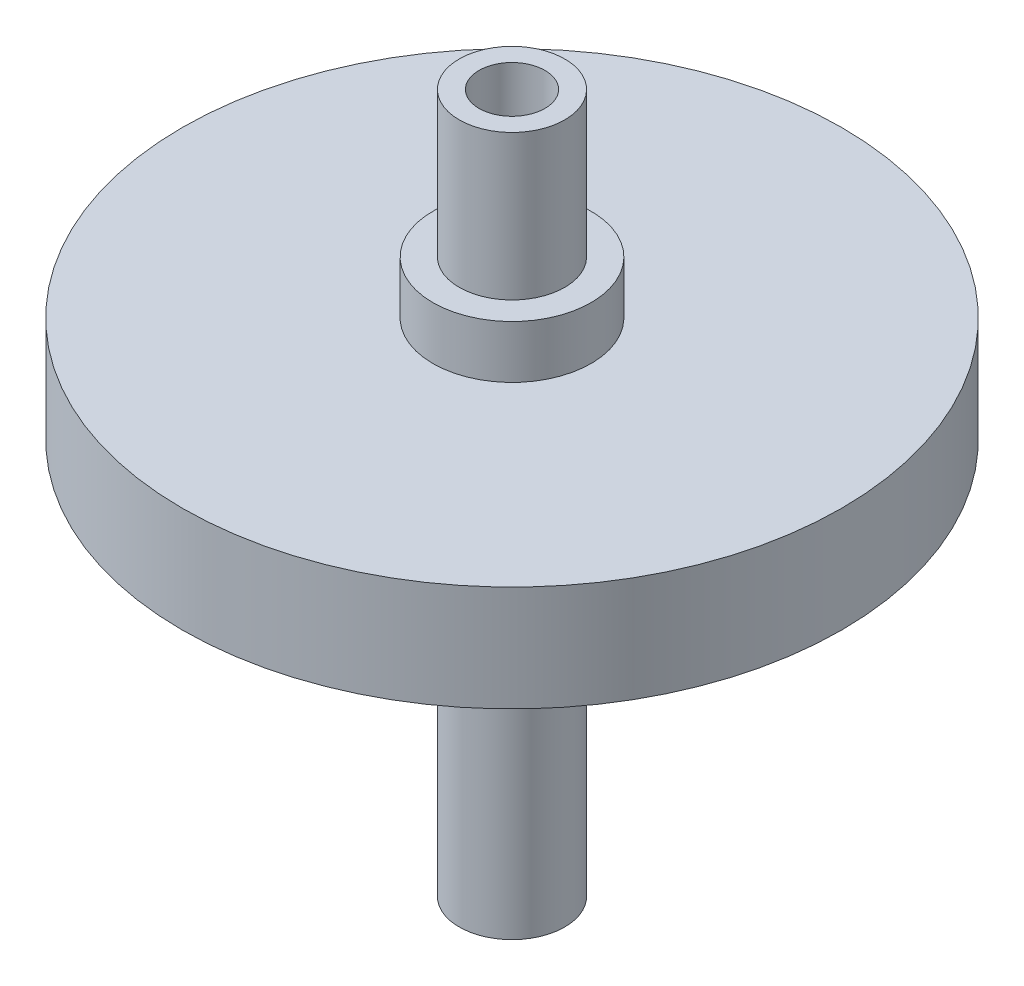
SolidWorks part; units mm, degrees
ref_plane "Front Plane" through (0, 0, 0) normal (0, 0, 1) x (1, 0, 0)
ref_plane "Top Plane" through (0, 0, 0) normal (0, 1, 0) x (1, 0, 0)
ref_plane "Right Plane" through (0, 0, 0) normal (1, 0, 0) x (0, 0, -1)
sketch "Sketch1" plane through (0, 0, 0) normal (0, 1, 0) x (1, 0, 0)
  circle A0 centre (0, 0) radius 25
  dimension "D1" = 50
extrude "Boss-Extrude1" add sketch "Sketch1" along normal blind 8
sketch "Sketch2" plane through (0, 8, 0) normal (0, 1, 0) x (1, 0, 0)
  circle A0 centre (0, 0) radius 4
extrude "Boss-Extrude2" add sketch "Sketch2" along normal blind 15
sketch "Sketch3" plane through (0, 0, 0) normal (0, -1, 0) x (1, 0, 0)
  circle A0 centre (0, 0) radius 4
  dimension "D1" = 8
extrude "Boss-Extrude3" add sketch "Sketch3" along normal blind 30
sketch "Sketch4" plane through (0, 23, 0) normal (0, 1, 0) x (1, 0, 0)
  circle A0 centre (0, 0) radius 2.5
  dimension "D1" = 5
extrude "Cut-Extrude1" cut sketch "Sketch4" against normal through all both and the other way through all
sketch "Sketch5" plane through (0, 0, 0) normal (0, -1, 0) x (1, 0, 0)
  circle A0 centre (0, 0) radius 6
extrude "Boss-Extrude4" add sketch "Sketch5" along normal blind 4
sketch "Sketch6" plane through (0, 8, 0) normal (0, 1, 0) x (1, 0, 0)
  circle A0 centre (0, 0) radius 6
extrude "Boss-Extrude5" add sketch "Sketch6" along normal blind 4
